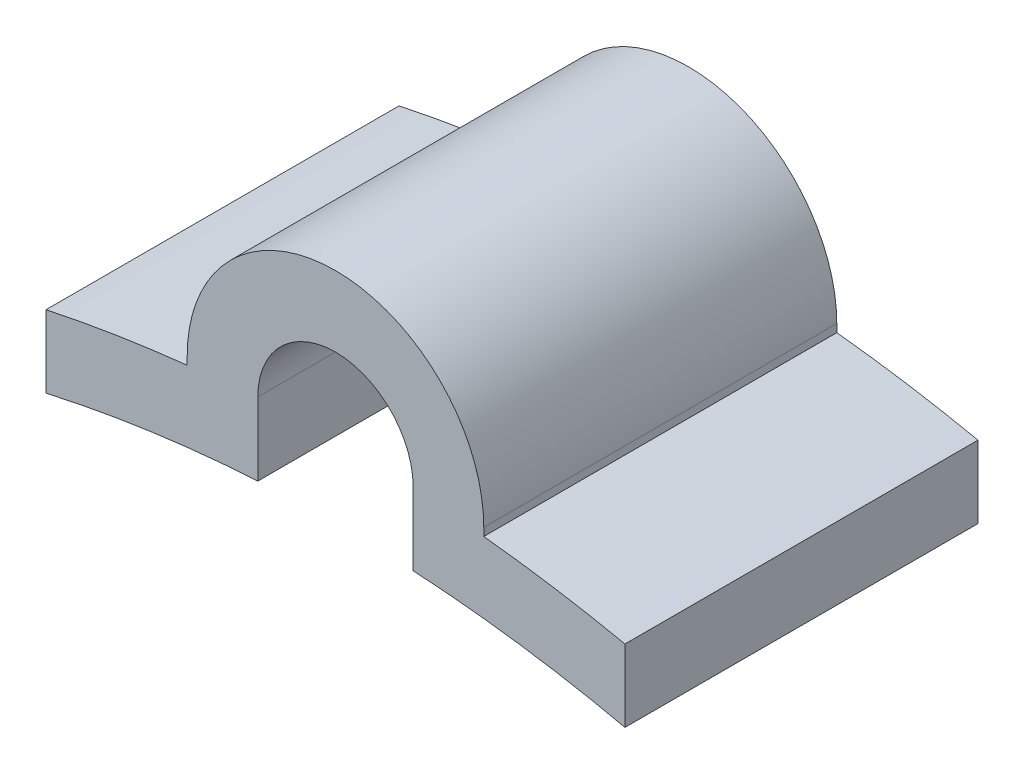
SolidWorks part; units mm, degrees
ref_plane "Front Plane" through (0, 0, 0) normal (0, 0, 1) x (1, 0, 0)
ref_plane "Top Plane" through (0, 0, 0) normal (0, 1, 0) x (1, 0, 0)
ref_plane "Right Plane" through (0, 0, 0) normal (1, 0, 0) x (0, 0, -1)
sketch "Sketch1" plane through (0, 0, 0) normal (0, 0, 1) x (1, 0, 0)
  line L0 (-4.2, 0) -> (-4.2, -0.2239)
  line L1 (4.2, 0) -> (4.2, -0.2239)
  line L2 (-2.2, 0) -> (-2.2, -2.0646)
  line L3 (2.2, 0) -> (2.2, -2.0646)
  line L7 (-8.2, -0.8605) -> (-8.2, -2.9075)
  line L8 (0, 7.7498) -> (0, -12.2814) construction
  line L9 (8.2, -0.8605) -> (8.2, -2.9075)
  circle A0 centre (0, 0) radius 2 construction
  arc A1 (2.2, 0) -> (-2.2, 0) centre (0, 0) ccw
  arc A2 (4.2, 0) -> (-4.2, 0) centre (0, 0) ccw
  circle A3 centre (0, 0) radius 4.2 construction
  circle A4 centre (0, 0) radius 2.2 construction
  arc A5 (-2.2, -2.0646) -> (-8.2, -2.9075) centre (0, -39.5) ccw
  arc A6 (-4.2, -0.2239) -> (-8.2, -0.8605) centre (0, -39.5) ccw
  circle A7 centre (0, -39.5) radius 39.5 construction
  circle A8 centre (0, -39.5) radius 37.5 construction
  arc A9 (8.2, -2.9075) -> (2.2, -2.0646) centre (0, -39.5) ccw
  arc A10 (8.2, -0.8605) -> (4.2, -0.2239) centre (0, -39.5) ccw
  dimension "D1" = 4
  dimension "D4" = 75
  dimension "D6" = 6
  dimension "D2" = 0.2
  dimension "D3" = 2
  dimension "D5" = 2
extrude "Boss-Extrude1" add sketch "Sketch1" along normal blind 10 contours A2 L0 A6 L7 A5 L2 A1 L3 A9 L9 A10 L1
equation "\"tube diameter\"= 4"
equation "\"D1@Sketch1\"=\"tube diameter\""
